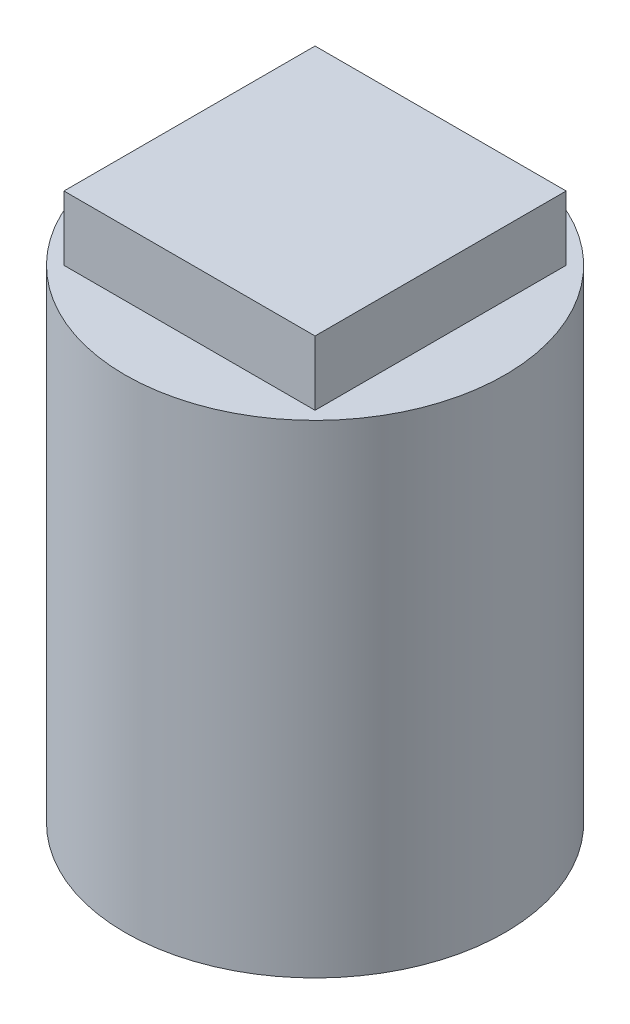
SolidWorks part; units mm, degrees
ref_plane "Front Plane" through (0, 0, 0) normal (0, 0, 1) x (1, 0, 0)
ref_plane "Top Plane" through (0, 0, 0) normal (0, 1, 0) x (1, 0, 0)
ref_plane "Right Plane" through (0, 0, 0) normal (1, 0, 0) x (0, 0, -1)
sketch "Sketch1" plane through (0, 0, 0) normal (0, 1, 0) x (1, 0, 0)
  circle A0 centre (0, 0) radius 2.95
  dimension "D1" = 5.9
extrude "Boss-Extrude1" add sketch "Sketch1" along normal blind 7.5
sketch "Sketch2" plane through (0, 7.5, 0) normal (0, 1, 0) x (1, 0, 0)
  line L1 (1.95, 1.95) -> (-1.95, 1.95)
  line L2 (1.95, 1.95) -> (1.95, -1.95)
  line L3 (1.95, -1.95) -> (-1.95, -1.95)
  line L4 (-1.95, 1.95) -> (-1.95, -1.95)
  line L5 (1.95, 1.95) -> (-1.95, -1.95) construction
  line L6 (1.95, -1.95) -> (-1.95, 1.95) construction
  point P0 (0, 0)
  dimension "D1" = 3.9
  dimension "D2" = 3.9
extrude "Boss-Extrude3" add sketch "Sketch2" along normal blind 1
